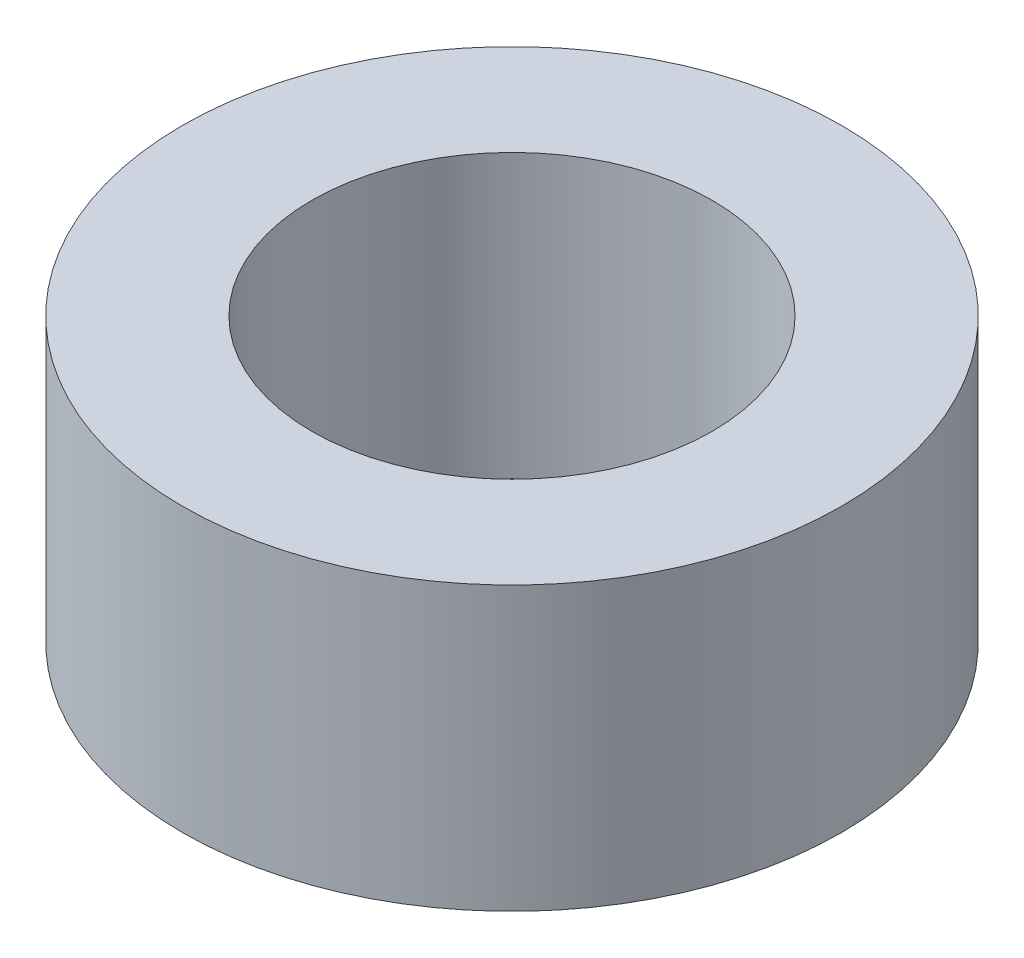
SolidWorks part; units mm, degrees
material "AISI 1020"
ref_plane "Front Plane" through (0, 0, 0) normal (0, 0, 1) x (1, 0, 0)
ref_plane "Top Plane" through (0, 0, 0) normal (0, 1, 0) x (1, 0, 0)
ref_plane "Right Plane" through (0, 0, 0) normal (1, 0, 0) x (0, 0, -1)
sketch "Sketch1" plane through (0, 0, 0) normal (0, 1, 0) x (1, 0, 0)
  circle A0 centre (0, 0) radius 2.125
  circle A1 centre (0, 0) radius 3.5
  dimension "D1" = 4.25
  dimension "D2" = 7
extrude "Boss-Extrude1" add sketch "Sketch1" along normal blind 3
